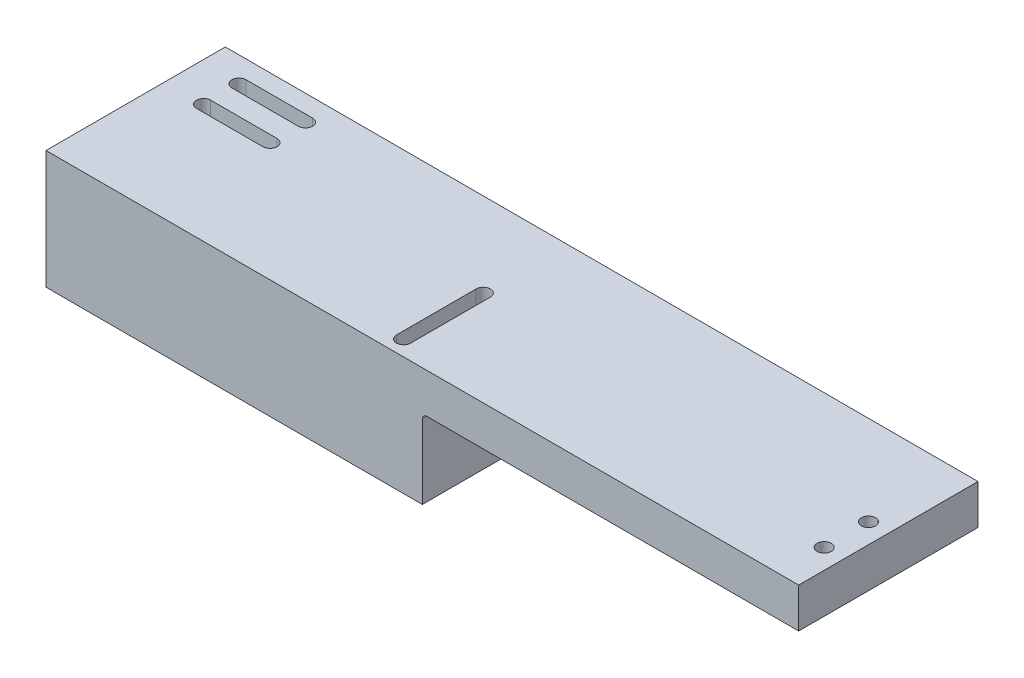
SolidWorks part; units mm, degrees
material "ABS PC"
ref_plane "Front Plane" through (0, 0, 0) normal (0, 0, 1) x (1, 0, 0)
ref_plane "Top Plane" through (0, 0, 0) normal (0, 1, 0) x (1, 0, 0)
ref_plane "Right Plane" through (0, 0, 0) normal (1, 0, 0) x (0, 0, -1)
sketch "Sketch1" plane through (0, 0, 0) normal (0, 1, 0) x (1, 0, 0)
  line L1 (-85, 20.25) -> (85, 20.25)
  line L2 (-85, 20.25) -> (-85, -20.25)
  line L3 (-85, -20.25) -> (85, -20.25)
  line L4 (85, 20.25) -> (85, -20.25)
  line L5 (-85, 20.25) -> (85, -20.25) construction
  line L6 (-85, -20.25) -> (85, 20.25) construction
  point P0 (0, 0)
extrude "Boss-Extrude1" add sketch "Sketch1" along normal blind 9
sketch "Sketch2" plane through (0, 0, 0) normal (0, -1, 0) x (1, 0, 0)
  line L0 (85, -20.25) -> (-85, -20.25) construction
  line L1 (-85, 20.25) -> (0, 20.25)
  line L2 (-85, 20.25) -> (-85, -20.25)
  line L3 (-85, -20.25) -> (0, -20.25)
  line L4 (0, 20.25) -> (0, -20.25)
extrude "Boss-Extrude2" add sketch "Sketch2" along normal blind 17.745
sketch "Sketch3" plane through (0, 9, 0) normal (0, 1, 0) x (1, 0, 0)
  line L0 (-76.2413, 6.5851) -> (-61.2413, 6.5851) construction
  line L1 (-76.2413, 8.1851) -> (-61.2413, 8.1851)
  line L2 (-76.2413, 4.9851) -> (-61.2413, 4.9851)
  line L3 (-61.2413, 14.5851) -> (-76.2413, 14.5851) construction
  line L4 (-61.2413, 12.9851) -> (-76.2413, 12.9851)
  line L5 (-61.2413, 16.1851) -> (-76.2413, 16.1851)
  line L6 (-7.7413, 1.2492) -> (-7.7413, -16.7508) construction
  line L7 (-6.1413, 1.2492) -> (-6.1413, -16.7508)
  line L8 (-9.3413, 1.2492) -> (-9.3413, -16.7508)
  arc A0 (-76.2413, 8.1851) -> (-76.2413, 4.9851) centre (-76.2413, 6.5851) ccw
  arc A1 (-61.2413, 4.9851) -> (-61.2413, 8.1851) centre (-61.2413, 6.5851) ccw
  arc A2 (-61.2413, 12.9851) -> (-61.2413, 16.1851) centre (-61.2413, 14.5851) ccw
  arc A3 (-76.2413, 16.1851) -> (-76.2413, 12.9851) centre (-76.2413, 14.5851) ccw
  arc A4 (-6.1413, 1.2492) -> (-9.3413, 1.2492) centre (-7.7413, 1.2492) ccw
  arc A5 (-9.3413, -16.7508) -> (-6.1413, -16.7508) centre (-7.7413, -16.7508) ccw
  circle A6 centre (80.5087, 0) radius 1.6
  circle A7 centre (80.5087, -10) radius 1.6
  point P2 (-68.7413, 6.5851)
  point P9 (-68.7413, 14.5851)
  point P18 (-7.7413, -7.7508)
extrude "Cut-Extrude1" cut sketch "Sketch3" against normal through all
fillet "Fillet1" radius 1 1 edges at (0, 0, 0)
